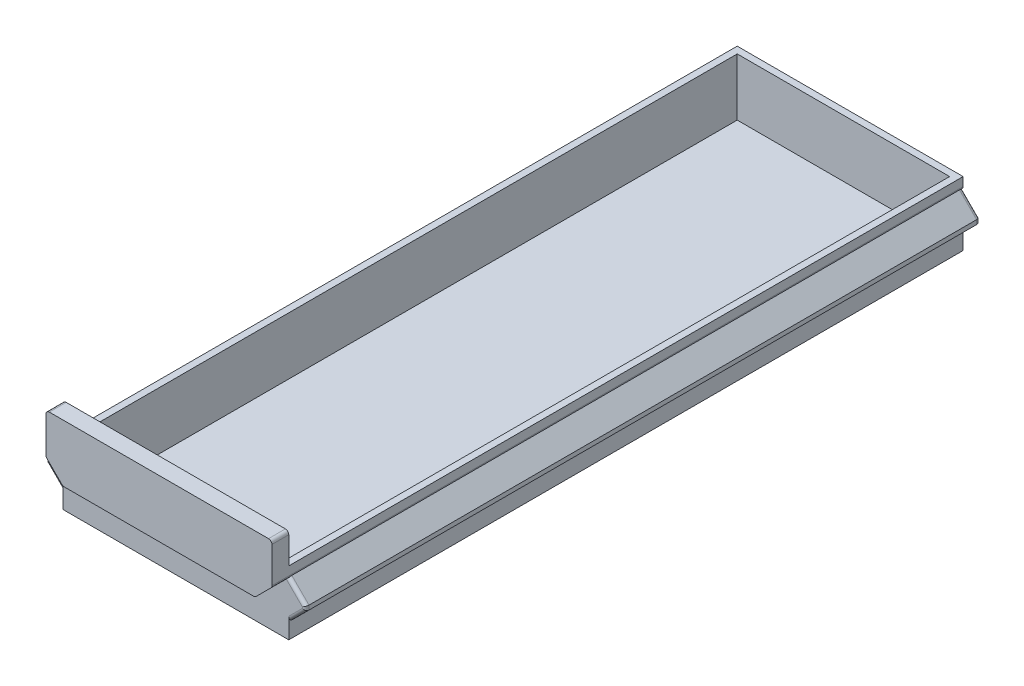
SolidWorks part; units mm, degrees
ref_plane "前视基准面" through (0, 0, 0) normal (0, 0, 1) x (1, 0, 0)
ref_plane "上视基准面" through (0, 0, 0) normal (0, 1, 0) x (1, 0, 0)
ref_plane "右视基准面" through (0, 0, 0) normal (1, 0, 0) x (0, 0, -1)
other "Configuration Table"
sketch "草图1" plane through (0, 0, 0) normal (0, 0, 1) x (1, 0, 0)
  line L0 (-6, 28) -> (-73, 28)
  line L1 (-73, 28) -> (-73, 32.6569)
  line L2 (-73, 32.6569) -> (-78, 37.6569)
  line L3 (-78, 37.6569) -> (-78, 38.9289)
  line L4 (-78, 38.9289) -> (-73, 43.9289)
  line L5 (-73, 43.9289) -> (-73, 47)
  line L6 (77, 47) -> (74, 47) construction
  line L7 (-73, 47) -> (-6, 47)
  line L8 (-39.5, 47) -> (-39.5, 28) construction
  line L9 (-83, 37) -> (-77, 31) construction
  line L10 (-77, 47) -> (-83, 41) construction
  line L11 (-83, 41) -> (-83, 37) construction
  line L12 (-74, 18) -> (-74, 23) construction
  line L13 (-6, 43.9289) -> (-6, 47)
  line L14 (-1, 38.9289) -> (-6, 43.9289)
  line L15 (-1, 37.6569) -> (-1, 38.9289)
  line L16 (-6, 32.6569) -> (-1, 37.6569)
  line L17 (-6, 28) -> (-6, 32.6569)
  point P14 (-78, 38.2929)
  dimension "D1" = 5
  dimension "D2" = 4
  dimension "D3" = 5
  dimension "D4" = 1
  dimension "D5" = 1
  dimension "D6" = 19
  dimension "D7" = 77
extrude "凸台-拉伸1" add sketch "草图1" against normal blind 200
sketch "草图2" plane through (0, 47, 0) normal (0, 1, 0) x (1, 0, 0)
  line L4 (-73, 0) -> (-6, 0)
  line L5 (-6, 0) -> (-6, 200)
  line L6 (-6, 200) -> (-73, 200)
  line L7 (-73, 200) -> (-73, 0)
  line L8 (-73, 0) -> (-6, 0)
  line L9 (-6, 0) -> (-6, 200)
  line L10 (-6, 200) -> (-73, 200)
  line L11 (-73, 200) -> (-73, 0)
  line L16 (-75, -2) -> (-4, -2)
  line L17 (-4, -2) -> (-4, 202)
  line L18 (-4, 202) -> (-75, 202)
  line L19 (-75, 202) -> (-75, -2)
  line L20 (-75, -2) -> (-4, -2)
  line L21 (-4, -2) -> (-4, 202)
  line L22 (-4, 202) -> (-75, 202)
  line L23 (-75, 202) -> (-75, -2)
  line L28 (-71, 2) -> (-8, 2)
  line L29 (-8, 2) -> (-8, 198)
  line L30 (-8, 198) -> (-71, 198)
  line L31 (-71, 198) -> (-71, 2)
  line L32 (-71, 2) -> (-8, 2)
  line L33 (-8, 2) -> (-8, 198)
  line L34 (-8, 198) -> (-71, 198)
  line L35 (-71, 198) -> (-71, 2)
  dimension "D1" = 0
  dimension "D2" = 2
  dimension "D3" = 2
extrude "切除-拉伸1" cut sketch "草图2" against normal offset from surface (17 mm away) 2 contours L34 L35 L32 L33 up to face at (-39.5, 28, -100)
sketch "草图4" plane through (0, 0, 0) normal (0, 0, 1) x (1, 0, 0)
  line L0 (87.5, 56) -> (-87.5, 56) construction
  line L1 (-73, 39) -> (-6, 39)
  line L2 (-73, 39) -> (-73, 56)
  line L3 (-73, 56) -> (-6, 56)
  line L4 (-6, 39) -> (-6, 56)
  line L5 (-73, 47) -> (-73, 43.9289) construction
  line L6 (-6, 43.9289) -> (-6, 47) construction
  line L7 (-6, 47) -> (-73, 47) construction
  dimension "8" = 8
extrude "凸台-拉伸2" add sketch "草图4" along normal blind 5
chamfer "倒角1" distance 5 angle 45 2 edges at (-73, 39, 2.5) (-6, 39, 2.5)
fillet "圆角1" radius 1 6 edges at (-68, 39, 2.5) (-73, 44, -97.5) (-11, 39, 2.5) (-6, 44, -97.5) (-6, 56, 2.5) (-73, 56, 2.5)
fillet "圆角3" radius 1 12 edges at (-75.5, 35.1569, 0) (-75.458, 41.4709, 0) (-78, 38.2929, 0) (-75.5, 35.1569, -200) (-78, 38.2929, -200) (-75.458, 41.4709, -200) (-3.5, 35.1569, -200) (-1, 38.2929, -200) (-3.542, 41.4709, -200) (-3.5, 35.1569, 0) (-1, 38.2929, 0) (-3.542, 41.4709, 0)
